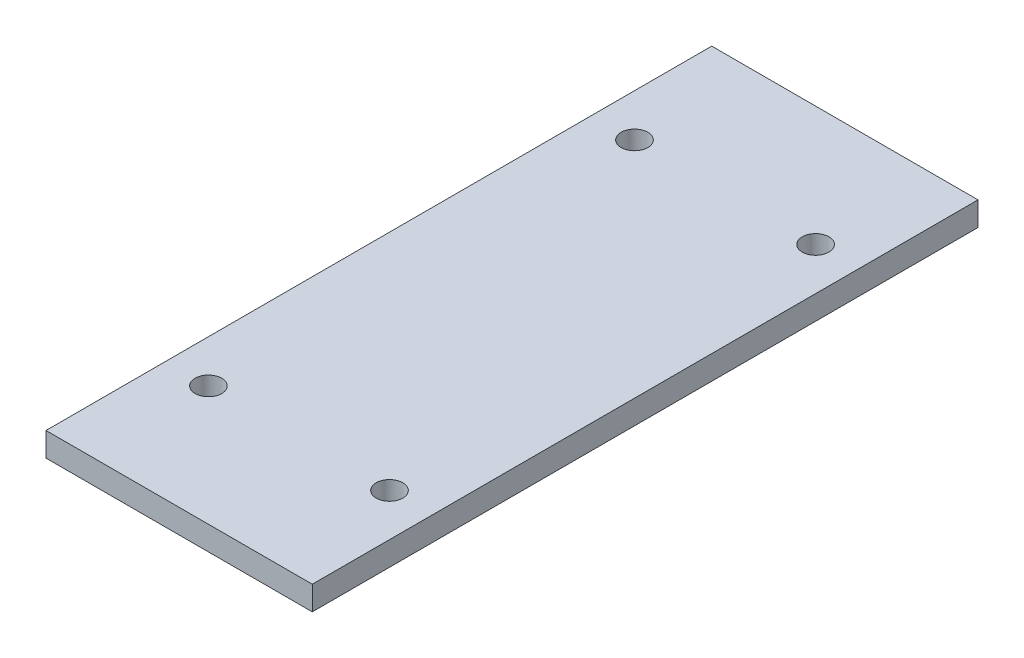
SolidWorks part; units mm, degrees
ref_plane "Front Plane" through (0, 0, 0) normal (0, 0, 1) x (1, 0, 0)
ref_plane "Top Plane" through (0, 0, 0) normal (0, 1, 0) x (1, 0, 0)
ref_plane "Right Plane" through (0, 0, 0) normal (1, 0, 0) x (0, 0, -1)
sketch "Sketch1" plane through (0, 0, 0) normal (0, 0, 1) x (1, 0, 0)
  line L1 (0, 0) -> (100, 0)
  line L2 (0, 0) -> (0, -9)
  line L3 (0, -9) -> (100, -9)
  line L4 (100, 0) -> (100, -9)
  dimension "D1" = 9
  dimension "D2" = 100
extrude "Boss-Extrude1" add sketch "Sketch1" along normal blind 250 contours L3 L4 L1 L2
sketch "Sketch2" plane through (0, 0, 0) normal (0, 1, 0) x (1, 0, 0)
  line L0 (100, -250) -> (100, 0) construction
  line L1 (0, -250) -> (0, 0) construction
  line L2 (0, 0) -> (100, 0) construction
  circle A0 centre (16, -45) radius 5
  circle A1 centre (84, -45) radius 5
  circle A2 centre (16, -205) radius 5
  circle A3 centre (84, -205) radius 5
  point P8 (0, 0)
  point P9 (0, 0)
  point P10 (0, 0)
  point P11 (0, 0)
  point P18 (0, 0)
  point P19 (0, 0)
  dimension "D1" = 10
  dimension "D2" = 10
  dimension "D3" = 10
  dimension "D4" = 10
  dimension "D5" = 160
  dimension "D6" = 16
  dimension "D7" = 16
  dimension "D8" = 45
extrude "Cut-Extrude2" cut sketch "Sketch2" against normal through all
equation "\"D7@Sketch2\"=\"D6@Sketch2\""
